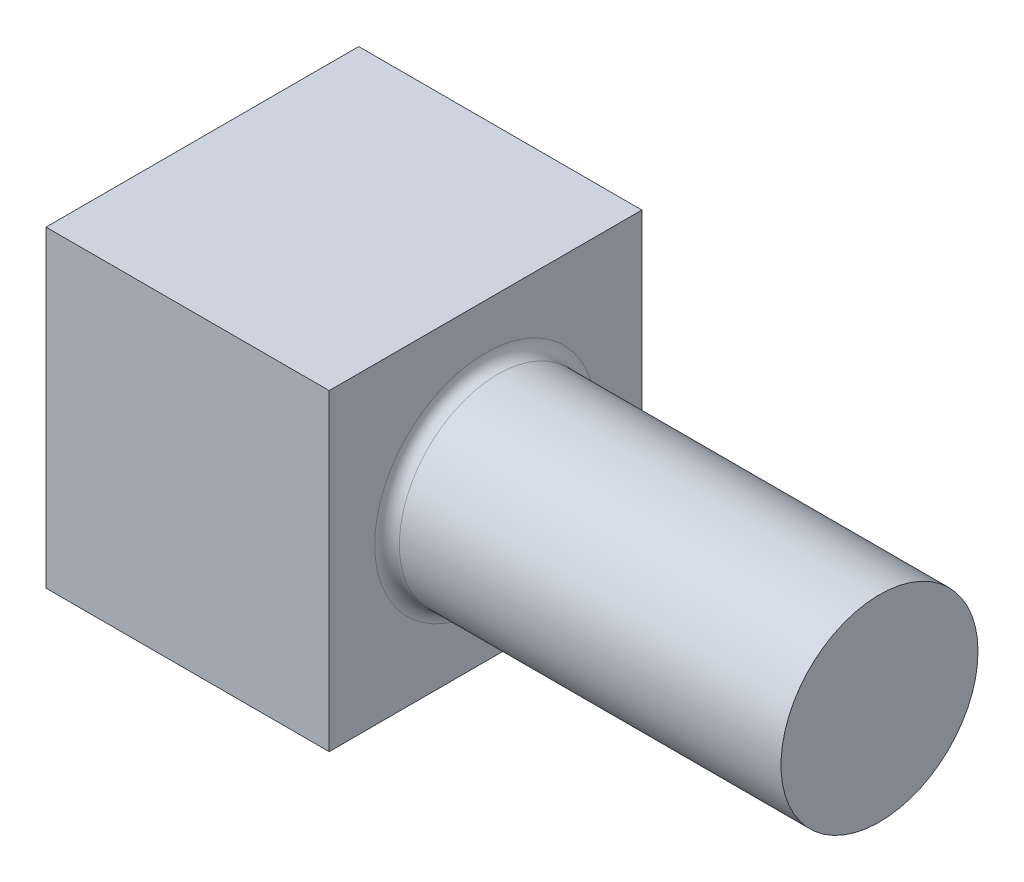
SolidWorks part; units mm, degrees
material "Low Carbon Steel"
ref_plane "Front Plane" through (0, 0, 0) normal (0, 0, 1) x (1, 0, 0)
ref_plane "Top Plane" through (0, 0, 0) normal (0, 1, 0) x (1, 0, 0)
ref_plane "Right Plane" through (0, 0, 0) normal (1, 0, 0) x (0, 0, -1)
sketch "Sketch1" plane through (0, 0, 0) normal (1, 0, 0) x (0, 0, -1)
  line L0 (-6.35, 6.35) -> (6.35, -6.35) construction
  line L1 (-6.35, 6.35) -> (6.35, 6.35)
  line L2 (-6.35, 6.35) -> (-6.35, -6.35)
  line L3 (-6.35, -6.35) -> (6.35, -6.35)
  line L4 (6.35, 6.35) -> (6.35, -6.35)
  dimension "D1" = 12.7
extrude "Boss-Extrude1" add sketch "Sketch1" along normal blind 12
sketch "Sketch2" plane through (12, 0, 0) normal (1, 0, 0) x (0, 0, -1)
  circle A0 centre (0, 0) radius 4
  dimension "D1" = 8
extrude "Boss-Extrude2" add sketch "Sketch2" along normal blind 16
cosmetic thread "Cosmetic Thread2" parameters "D1"=15, "D2"=6.619
fillet "Fillet1" radius 0.5 1 edges at (12, 0, -4)
chamfer "Chamfer2" distance 0.5 angle 45 4 edges at (0, 6.35, 0) (0, 0, 6.35) (0, -6.35, 0) (0, 0, -6.35)
